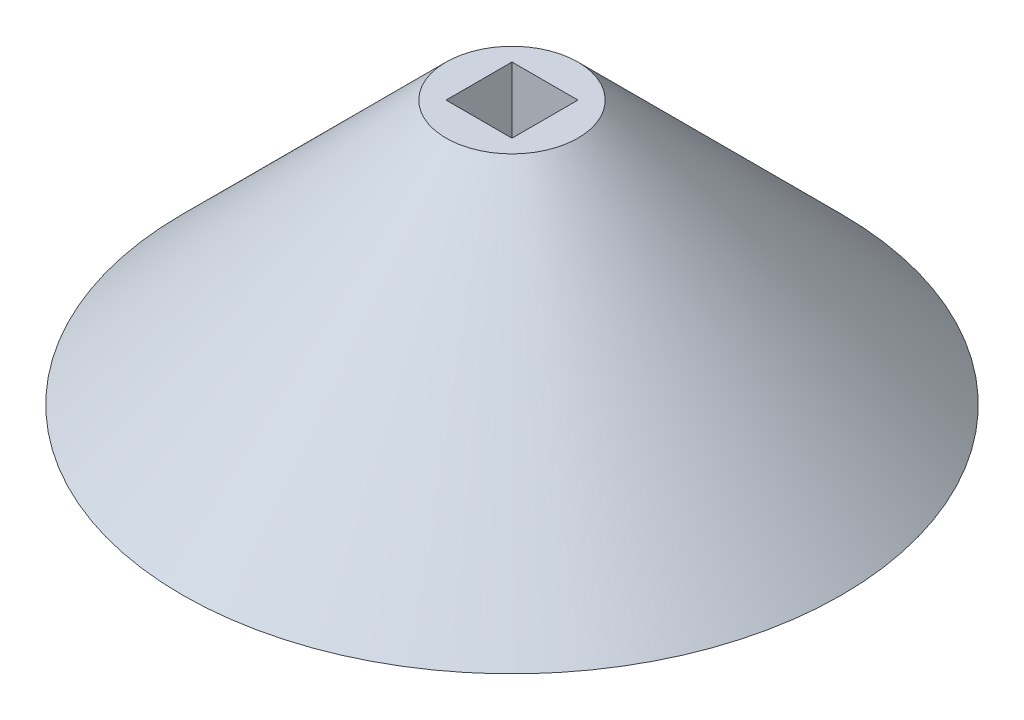
SolidWorks part; units mm, degrees
ref_plane "Front Plane" through (0, 0, 0) normal (0, 0, 1) x (1, 0, 0)
ref_plane "Top Plane" through (0, 0, 0) normal (0, 1, 0) x (1, 0, 0)
ref_plane "Right Plane" through (0, 0, 0) normal (1, 0, 0) x (0, 0, -1)
sketch "Sketch1" plane through (0, 0, 0) normal (1, 0, 0) x (0, 0, -1)
  line L3 (0, 0) -> (0, 30) construction
  line L4 (0, 0) -> (0, 31.6994) construction
  line L5 (0, 0) -> (25, 0)
  line L6 (25, 0) -> (5, 20)
  line L7 (5, 20) -> (0, 20)
  line L8 (0, 20) -> (0, 0)
  dimension "D1" = 25
  dimension "D2" = 30
  dimension "D3" = 5
  dimension "D4" = 20
revolve "Revolve1" add sketch "Sketch1" angle 360 about L4
sketch "Sketch2" plane through (0, 0, 0) normal (0, 1, 0) x (1, 0, 0)
  circle A0 centre (0, 0) radius 1.5
  dimension "D1" = 3
extrude "Cut-Extrude1" cut sketch "Sketch2" along normal through all
sketch "Sketch3" plane through (0, 0, 0) normal (0, 1, 0) x (1, 0, 0)
  line L1 (-2.5, -2.5) -> (2.5, -2.5)
  line L2 (-2.5, -2.5) -> (-2.5, 2.5)
  line L3 (-2.5, 2.5) -> (2.5, 2.5)
  line L4 (2.5, -2.5) -> (2.5, 2.5)
  line L5 (-2.5, -2.5) -> (2.5, 2.5) construction
  line L6 (-2.5, 2.5) -> (2.5, -2.5) construction
  point P0 (0, 0)
  dimension "D1" = 5
  dimension "D2" = 5
extrude "Cut-Extrude2" cut sketch "Sketch3" along normal through all from offset 10
sketch "Sketch4" plane through (0, 0, 0) normal (0, 1, 0) x (1, 0, 0)
  circle A0 centre (0, 0) radius 13.1
  dimension "D1" = 26.2
extrude "Cut-Extrude3" cut sketch "Sketch4" along normal blind 7.9
